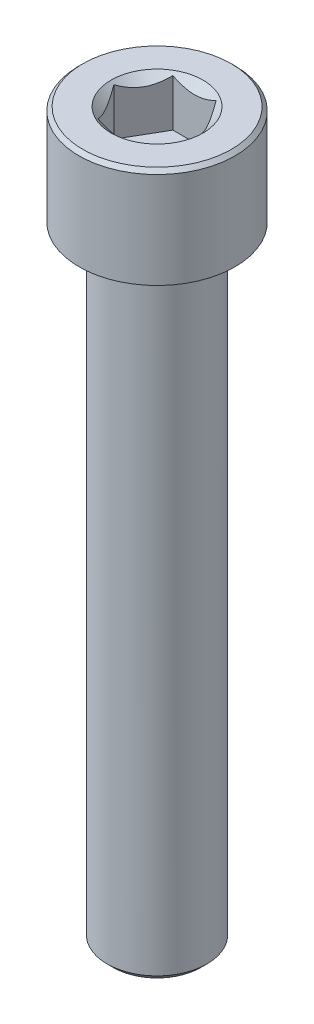
SolidWorks part; units mm, degrees
ref_plane "Płaszczyzna przednia" through (0, 0, 0) normal (0, 0, 1) x (1, 0, 0)
ref_plane "Płaszczyzna górna" through (0, 0, 0) normal (0, 1, 0) x (1, 0, 0)
ref_plane "Płaszczyzna prawa" through (0, 0, 0) normal (1, 0, 0) x (0, 0, -1)
sketch "Szkic1" plane through (0, 0, 0) normal (0, 0, 1) x (1, 0, 0)
  line L0 (0, 0) -> (0, 67.7826) construction
  line L1 (0, 0) -> (-4, 0)
  line L2 (-4, 0) -> (-4, 50)
  line L3 (-4, 50) -> (-6.25, 50)
  line L4 (-6.25, 50) -> (-6.25, 58)
  line L5 (-6.25, 58) -> (0, 58)
  line L6 (0, 58) -> (0, 0)
  dimension "D1" = 12.5
  dimension "D2" = 8
  dimension "D3" = 8
  dimension "D4" = 50
revolve "Obrót1" add sketch "Szkic1" angle 360 about L0
cosmetic thread "Oznaczenie gwintu1" parameters "D2"=6.619
sketch "Szkic2" plane through (0, 58, 0) normal (0, 1, 0) x (1, 0, 0)
  line L0 (0, 0) -> (5.3969, 0) construction
  line L1 (3.4641, 0) -> (1.7321, 3)
  line L2 (1.7321, 3) -> (-1.7321, 3)
  line L3 (-1.7321, 3) -> (-3.4641, 0)
  line L4 (-3.4641, 0) -> (-1.7321, -3)
  line L5 (-1.7321, -3) -> (1.7321, -3)
  line L6 (1.7321, -3) -> (3.4641, 0)
  circle A0 centre (0, 0) radius 3 construction
  dimension "D1" = 6
extrude "Wyciągnięcie1" cut sketch "Szkic2" against normal blind 4
chamfer "Sfazowanie1" distance 0.3 angle 45 1 edges at (0, 58, -6.25)
sketch "Szkic3" plane through (0, 58, 0) normal (0, 1, 0) x (1, 0, 0)
  circle A0 centre (0, 0) radius 3.6817
extrude "Wytnij-wyciągnięcie1" cut sketch "Szkic3" against normal blind 2 draft 45
chamfer "Sfazowanie2" distance 0.5 angle 45 1 edges at (0, 0, -4)
